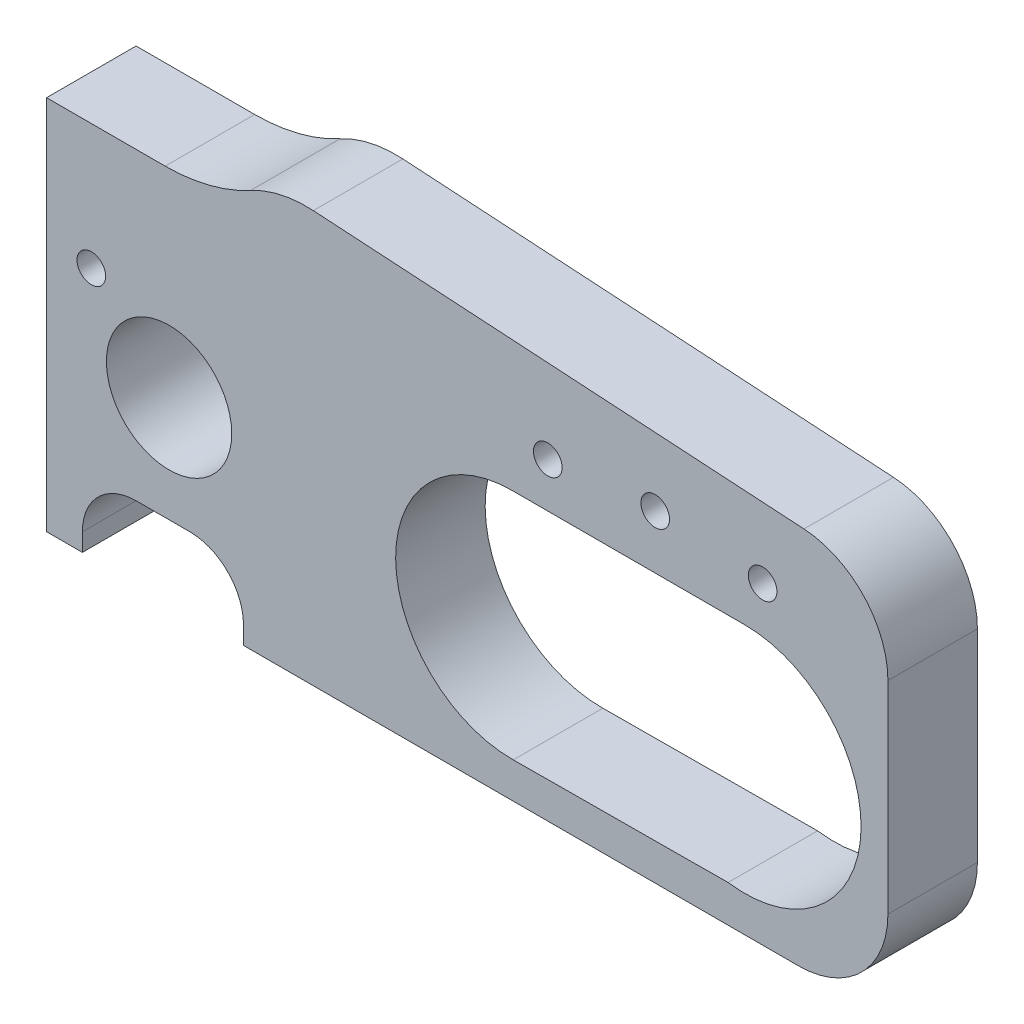
SolidWorks part; units mm, degrees
ref_plane "Front Plane" through (0, 0, 0) normal (1, 0, 0) x (0, 1, 0)
ref_plane "Top Plane" through (0, 0, 0) normal (0, 0, 1) x (0, 1, 0)
ref_plane "Right Plane" through (0, 0, 0) normal (0, 1, 0) x (-1, 0, 0)
sketch "Sketch1" plane through (0, 0, 0) normal (0, 0, 1) x (0, 1, 0)
  line L0 (12.9142, -18.3709) -> (14.6113, 9.0364)
  line L1 (7.9237, -23.0618) -> (-3.3763, -23.0618)
  line L4 (-8.3763, 23.9382) -> (12.6237, 23.9382)
  line L5 (12.6237, 23.9382) -> (12.6237, 17.3122)
  line L7 (-6.3763, -2.0618) -> (-6.2989, -16.0618)
  line L8 (6.6237, -15.0618) -> (6.6237, -2.0618)
  line L10 (-8.3763, 23.9382) -> (-8.3763, -18.0618)
  arc A2 (14.6113, 9.0364) -> (13.8358, 12.54) centre (8.1237, 9.4382) ccw
  arc A3 (12.6237, 17.3122) -> (13.8358, 12.54) centre (22.6237, 17.3122) ccw
  arc A4 (-8.3763, -18.0618) -> (-3.3763, -23.0618) centre (-3.3763, -18.0618) ccw
  arc A5 (7.9237, -23.0618) -> (12.9142, -18.3709) centre (7.9237, -18.0618) ccw
  circle A8 centre (5.6237, 21.4382) radius 0.8
  circle A9 centre (9.1237, -4.0618) radius 0.8
  circle A10 centre (9.6237, -10.0618) radius 0.8
  circle A11 centre (9.1237, -16.0618) radius 0.8
  arc A12 (6.6237, -2.0618) -> (-6.3759, -2.1337) centre (0.1237, -2.0618) ccw
  arc A13 (-6.3096, -14.1329) -> (6.6237, -15.0618) centre (0.1237, -15.0618) ccw
  circle A16 centre (8.1237, 9.4382) radius 5.1
  circle A18 centre (8.1237, 9.4382) radius 5.1
  circle A23 centre (1.537, 17.0949) radius 3.5
  dimension "D8" = 2.5
  dimension "D9" = 1.6
  dimension "D10" = 1.6
  dimension "D11" = 7
  dimension "D1" = 21
  dimension "D2" = 42
  dimension "D3" = 27.4598
  dimension "D4" = 11.3
  dimension "D5" = 2.5
  dimension "D6" = 2.5
  dimension "D7" = 3
extrude "Boss-Extrude1" add sketch "Sketch1" along normal blind 5
sketch "Sketch2" plane through (-23.9382, 0, 0) normal (-1, 0, 0) x (0, -1, 0)
  line L0 (-12.6237, 2.5) -> (-9.6237, 2.5) construction
  line L1 (-12.6237, 5) -> (-12.6237, 0) construction
  line L2 (8.3763, 5) -> (8.3763, 0) construction
  circle A0 centre (-9.6237, 2.5) radius 1.25
  circle A1 centre (2.8763, 2.5) radius 1.25
  dimension "D2" = 5.5
  dimension "D3" = 2.5
  dimension "D4" = 2.5
  dimension "D1" = 3
  dimension "D5" = 0
extrude "Cut-Extrude1" cut sketch "Sketch2" against normal blind 5
sketch "Sketch21" plane through (0, 0, 5) normal (0, 0, 1) x (1, 0, 0)
  circle A0 centre (-9.4382, 8.1237) radius 5.1
extrude "Boss-Extrude2" add sketch "Sketch21" against normal blind 1
sketch "Sketch22" plane through (0, 0, 0) normal (0, 0, -1) x (1, 0, 0)
  line L0 (-23.9382, 8.3763) -> (-23.9382, -12.6237) construction
  line L1 (-21.9382, 8.3763) -> (-12.9382, 8.3763)
  line L2 (-21.9382, 8.3763) -> (-21.9382, 4.3763)
  line L3 (-21.9382, 4.3763) -> (-12.9382, 4.3763)
  line L4 (-12.9382, 8.3763) -> (-12.9382, 4.3763)
  line L5 (-21.9382, 8.3763) -> (-12.9382, 4.3763) construction
  line L6 (-21.9382, 4.3763) -> (-12.9382, 8.3763) construction
  line L7 (-23.9382, 8.3763) -> (18.0618, 8.3763) construction
  point P0 (-17.4382, 6.3763)
  point P5 (-11.6911, 5.9432)
  point P8 (-7.0067, 8.3763)
  dimension "D1" = 2
  dimension "D2" = 4
  dimension "D3" = 9
extrude "Cut-Extrude2" cut sketch "Sketch22" against normal blind 10
fillet "Fillet1" radius 3 2 edges at (-12.9382, -4.3763, 2.5) (-21.9382, -4.3763, 2.5)
